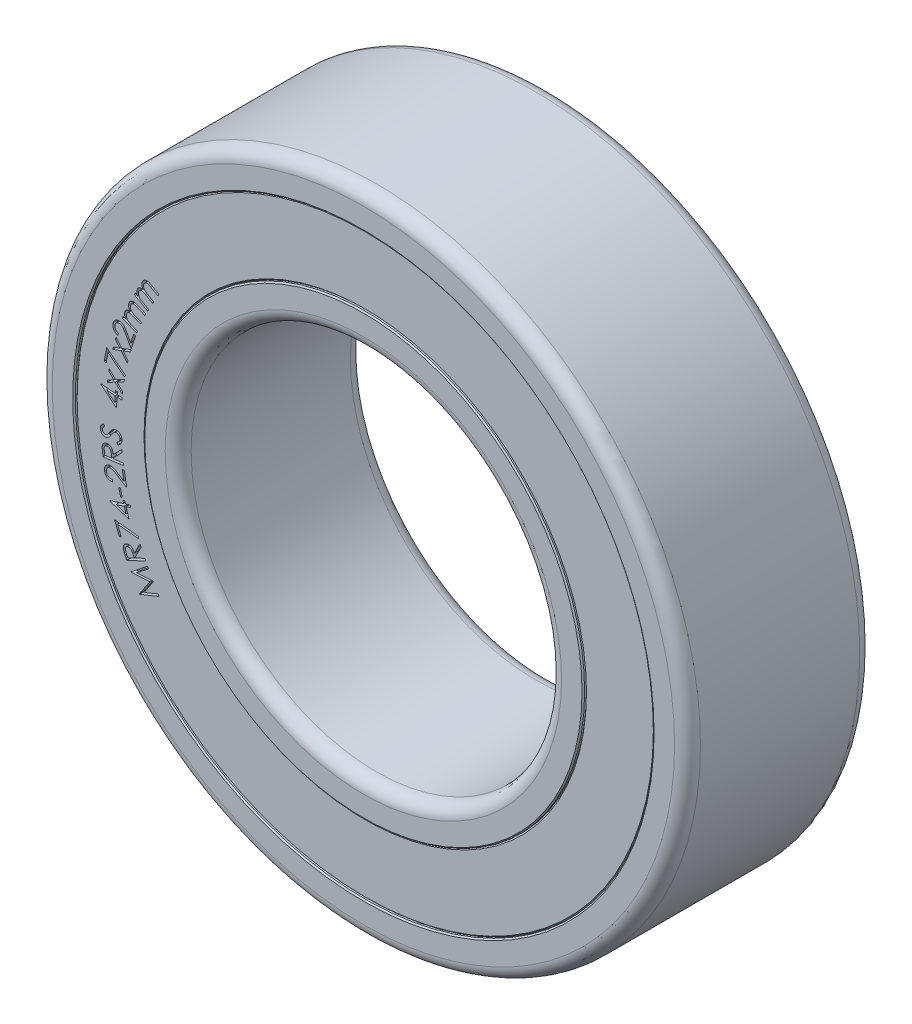
SolidWorks part; units mm, degrees
material "AISI 316 Annealed Stainless Steel Bar (SS)"
ref_plane "Front" through (0, 0, 0) normal (0, 0, 1) x (1, 0, 0)
ref_plane "Top" through (0, 0, 0) normal (0, 1, 0) x (1, 0, 0)
ref_plane "Right" through (0, 0, 0) normal (1, 0, 0) x (0, 0, -1)
sketch "LAYOUT R" plane through (0, 0, 0) normal (1, 0, 0) x (0, 0, -1)
  line L0 (-1, 2) -> (1, 2)
  line L1 (1, -3.5) -> (-1, -3.5) construction
  line L2 (1, -3.5) -> (1, 3.5) construction
  line L3 (1, 3.5) -> (-1, 3.5)
  line L4 (-1, -3.5) -> (-1, 3.5) construction
  line L5 (1, -3.5) -> (-1, 3.5) construction
  line L6 (1, 3.5) -> (-1, -3.5) construction
  line L7 (-1, 2.375) -> (1, 2.375)
  line L8 (-1, 3.125) -> (1, 3.125)
  line L11 (-17.5, 0) -> (17.5, 0) construction
  line L12 (-1, 3.5) -> (-1, 3.125)
  line L13 (1, 3.5) -> (1, 3.125)
  line L14 (-1, 3.125) -> (-1, 2.375)
  line L15 (1, 3.125) -> (1, 2.375)
  line L16 (-1, 2.375) -> (-1, 2)
  line L17 (1, 2.375) -> (1, 2)
  line L18 (-0.98, 3.125) -> (-0.98, 2.375)
  line L19 (0.98, 3.125) -> (0.98, 2.375)
  point P0 (0, 0)
  point P15 (0, 0)
  dimension "D1" = 2
  dimension "D2" = 7
  dimension "D3" = 2
  dimension "D6" = 0.02
  dimension "D7" = 0.02
  dimension "D4" = 2.375
  dimension "D5" = 3.125
sketch "Sketch R, INNER BODY" plane through (0, 0, 0) normal (1, 0, 0) x (0, 0, -1)
  line L0 (-1, 2) -> (1, 2) construction
  line L2 (-1, 2.375) -> (1, 2.375) construction
  line L4 (-1, 2) -> (1, 2)
  line L6 (-1, 2.375) -> (1, 2.375)
  line L8 (1, 2.375) -> (1, 2) construction
  line L9 (-1, 2.375) -> (-1, 2) construction
  line L10 (1, 2.375) -> (1, 2)
  line L11 (-1, 2.375) -> (-1, 2)
  line L12 (-17.5, 0) -> (17.5, 0) construction
  line L13 (-17.5, 0) -> (17.5, 0) construction
sketch "Sketch R, OUTER BODY" plane through (0, 0, 0) normal (1, 0, 0) x (0, 0, -1)
  line L2 (-1, 3.125) -> (1, 3.125) construction
  line L3 (1, 3.5) -> (-1, 3.5) construction
  line L6 (-1, 3.125) -> (1, 3.125)
  line L7 (1, 3.5) -> (-1, 3.5)
  line L8 (-17.5, 0) -> (17.5, 0) construction
  line L9 (-17.5, 0) -> (17.5, 0) construction
  line L10 (1, 3.5) -> (1, 3.125) construction
  line L11 (-1, 3.5) -> (-1, 3.125) construction
  line L12 (1, 3.5) -> (1, 3.125)
  line L13 (-1, 3.5) -> (-1, 3.125)
sketch "Sketch R, SEAL FACES" plane through (0, 0, 0) normal (1, 0, 0) x (0, 0, -1)
  line L0 (-17.5, 0) -> (17.5, 0) construction
  line L1 (-17.5, 0) -> (17.5, 0) construction
  line L3 (-1, 2.375) -> (1, 2.375) construction
  line L5 (-1, 3.125) -> (1, 3.125) construction
  line L7 (-0.98, 2.375) -> (0.98, 2.375)
  line L9 (-0.98, 3.125) -> (0.98, 3.125)
  line L10 (0.98, 3.125) -> (0.98, 2.375) construction
  line L11 (-0.98, 3.125) -> (-0.98, 2.375) construction
  line L12 (0.98, 3.125) -> (0.98, 2.375)
  line L13 (-0.98, 3.125) -> (-0.98, 2.375)
revolve "Revolve INNER BODY" add sketch "Sketch R, INNER BODY" angle 360 about L13
fillet "Fillet INNER BODY" radius 0.14 2 edges at (2, 0, 1) (2, 0, -1)
chamfer "Chamfer INNER BODY" distance 0.014 angle 45 2 edges at (2.375, 0, -1) (2.375, 0, 1)
revolve "Revolve OUTER BODY" add sketch "Sketch R, OUTER BODY" angle 360 about L9
fillet "Fillet OUTER BODY" radius 0.14 2 edges at (3.5, 0, -1) (3.5, 0, 1)
chamfer "Chamfer OUTER BODY" distance 0.014 angle 45 2 edges at (3.125, 0, 1) (3.125, 0, -1)
revolve "Revolve SEALS" add sketch "Sketch R, SEAL FACES" angle 360 about L1
chamfer "Chamfer SEALS" distance 0.014 angle 45 4 edges at (2.375, 0, -0.98) (3.125, 0, -0.98) (3.125, 0, 0.98) (2.375, 0, 0.98)
sketch "Sketch TEXT RADIUS 1 — MANUALLY ASSIGN TEXT AND FONT SIZE (FROM EQUATIONS)" plane through (0, 0, 0.98) normal (0, 0, 1) x (1, 0, 0)
  circle A0 centre (0, 0) radius 2.6375 construction
  text T0 "MR74-2RS  4x7x2mm" font "Century Gothic" height 0.225
  dimension "D1" = 5.275
extrude "Cut-Extrude SEAL LABEL 1" cut sketch "Sketch TEXT RADIUS 1 — MANUALLY ASSIGN TEXT AND FONT SIZE (FROM EQUATIONS)" against normal blind 0.05
sketch "Sketch TEXT RADIUS 2 — MANUALLY ASSIGN TEXT AND FONT SIZE (FROM EQUATIONS)" plane through (0, 0, -0.98) normal (0, 0, -1) x (-1, 0, 0)
  circle A0 centre (0, 0) radius 2.6375 construction
  text T0 "MR74-2RS  4x7x2mm" font "Century Gothic" height 0.225
  dimension "D1" = 5.275
extrude "Cut-Extrude SEAL LABEL 2" cut sketch "Sketch TEXT RADIUS 2 — MANUALLY ASSIGN TEXT AND FONT SIZE (FROM EQUATIONS)" against normal blind 0.05
equation "\"_i__BORE\"= 4"
equation "\"_i__OUTSIDE_DIAMETER\"= 7"
equation "\"_i__WIDTH\"= 2"
equation "\"_i_optional__TEXT_RADIUS_ADJUSTMENT\"= 0"
equation "\"_output__FONT_SIZE_mm\"= \"BODY_SPAN__SEAL__OF_RADIUS\" * \"param__FONT_SIZE_RATIO\"'MANUALLY ASSIGN TO FONT"
equation "\"BODY__HALF_WIDTH\"= \"_i__WIDTH\" / 2"
equation "\"BODY_SPAN___OF_DIAMETER\"= \"_i__OUTSIDE_DIAMETER\" - \"_i__BORE\""
equation "\"BODY_SPAN___OF_RADIUS\"= \"BODY_SPAN___OF_DIAMETER\" / 2"
equation "\"BODY_SPAN__BORE_AND_OD__OF RADIUS\"= ( \"BODY_SPAN___OF_RADIUS\" - \"BODY_SPAN__SEAL__OF_RADIUS\" ) / 2"
equation "\"BODY_SPAN__SEAL__OF_RADIUS\"= \"BODY_SPAN___OF_RADIUS\" * \"param__SEAL_PANEL_SPAN__RATIO_OF_BODY_RADIAN\""
equation "\"BORE__RADIUS\"= \"_i__BORE\" / 2"
equation "\"CORNER_RADII\"= \"_i__WIDTH\" * \"param__CORNER_RADII__ISO_MAX_RATIO_TO_WIDTH\""
equation "\"param__CORNER_RADII__ISO_MAX_RATIO_TO_WIDTH\"= 0.07'WHERE WIDTH IS LESS THAN DIAMETER"
equation "\"param__FONT_SIZE_RATIO\"= 0.3"
equation "\"param__SEAL_FACE_INSET__RATIO_OF_WIDTH\"= .01"
equation "\"param__SEAL_PANEL_SPAN__RATIO_OF_BODY_RADIAN\"= 0.5"
equation "\"param__SIDE_CHAMFERS__RATIO_TO_OD\"= 1 / 500"
equation "\"RING_INNER__OUTSIDE_RADIUS\"= \"BORE__RADIUS\" + \"BODY_SPAN__BORE_AND_OD__OF RADIUS\""
equation "\"RING_OUTER__OUTSIDE_RADIUS\"= ( \"_i__OUTSIDE_DIAMETER\" / 2 ) - \"BODY_SPAN__BORE_AND_OD__OF RADIUS\""
equation "\"SEAL_FACE_INSET\"= \"_i__WIDTH\" * \"param__SEAL_FACE_INSET__RATIO_OF_WIDTH\""
equation "\"SIDE_FACE_AND_SEAL_CHAMFERS\"= \"_i__OUTSIDE_DIAMETER\" * \"param__SIDE_CHAMFERS__RATIO_TO_OD\""
equation "\"TEXT_RADIUS\"= \"_i__BORE\" + ( \"BODY_SPAN___OF_DIAMETER\" / 2 ) - \"_output__FONT_SIZE_mm\" + \"_i_optional__TEXT_RADIUS_ADJUSTMENT\""
equation "\"D1@Chamfer INNER BODY\"=\"SIDE_FACE_AND_SEAL_CHAMFERS\""
equation "\"D1@Chamfer OUTER BODY\"=\"SIDE_FACE_AND_SEAL_CHAMFERS\""
equation "\"D1@Chamfer SEALS\"=\"SIDE_FACE_AND_SEAL_CHAMFERS\""
equation "\"D1@Fillet INNER BODY\"=\"CORNER_RADII\""
equation "\"D1@Fillet OUTER BODY\"=\"CORNER_RADII\""
equation "\"D1@LAYOUT R\"=\"_i__WIDTH\""
equation "\"D1@Sketch TEXT RADIUS 1 — MANUALLY ASSIGN TEXT AND FONT SIZE (FROM EQUATIONS)\" = \"TEXT_RADIUS\""
equation "\"D1@Sketch TEXT RADIUS 2 — MANUALLY ASSIGN TEXT AND FONT SIZE (FROM EQUATIONS)\" = \"TEXT_RADIUS\""
equation "\"D2@LAYOUT R\"=\"_i__OUTSIDE_DIAMETER\""
equation "\"D3@LAYOUT R\"=\"BORE__RADIUS\""
equation "\"D4@LAYOUT R\"=\"RING_INNER__OUTSIDE_RADIUS\""
equation "\"D5@LAYOUT R\"=\"RING_OUTER__OUTSIDE_RADIUS\""
